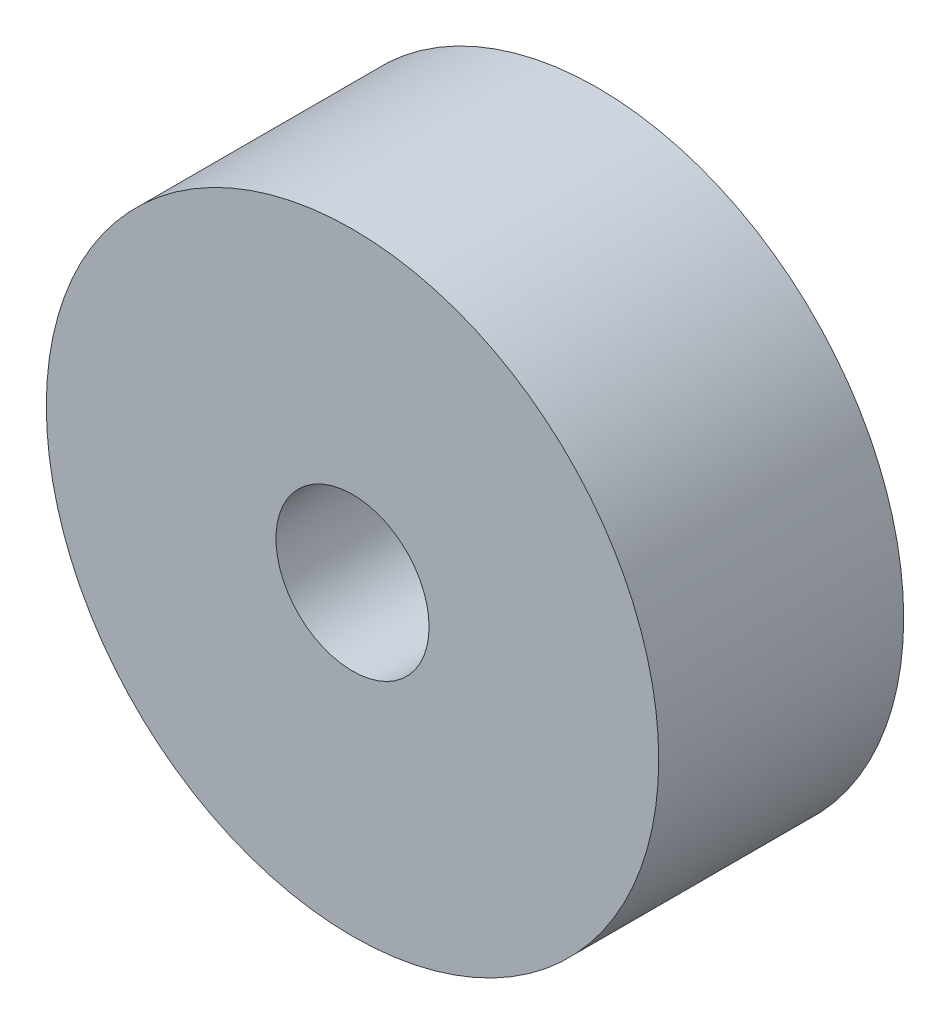
SolidWorks part; units mm, degrees
material "延性铁 (SN)"
ref_plane "前视基准面" through (0, 0, 0) normal (0, 0, 1) x (1, 0, 0)
ref_plane "上视基准面" through (0, 0, 0) normal (0, 1, 0) x (1, 0, 0)
ref_plane "右视基准面" through (0, 0, 0) normal (1, 0, 0) x (0, 0, -1)
sketch "草图1" plane through (0, 0, 0) normal (0, 0, 1) x (1, 0, 0)
  circle A0 centre (0, 0) radius 2.5
  circle A1 centre (0, 0) radius 10
  dimension "D1" = 5
  dimension "D2" = 20
extrude "凸台-拉伸1" add sketch "草图1" along normal blind 8
